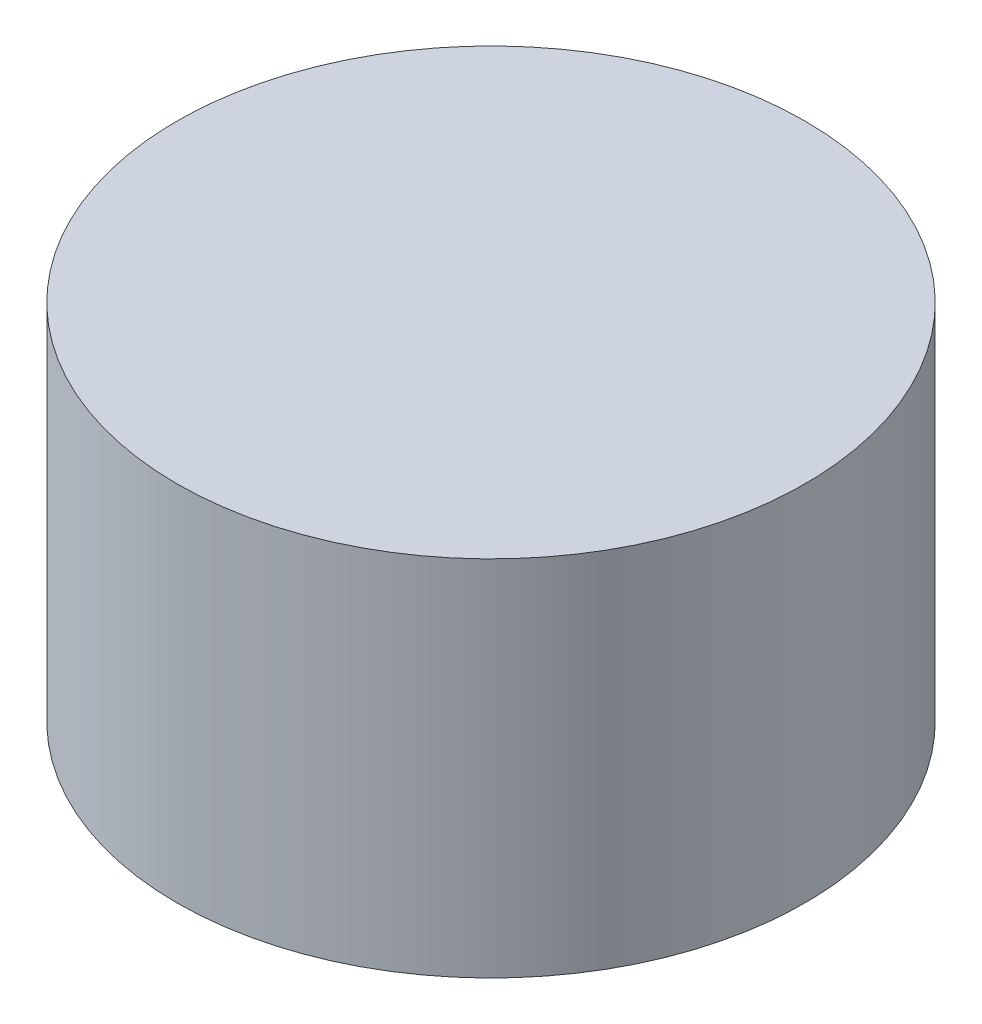
SolidWorks part; units mm, degrees
material "Бутил"
ref_plane "Спереди (XY)" through (0, 0, 0) normal (0, 0, 1) x (1, 0, 0)
ref_plane "Сверху (XZ)" through (0, 0, 0) normal (0, 1, 0) x (1, 0, 0)
ref_plane "Справа (ZY)" through (0, 0, 0) normal (1, 0, 0) x (0, 0, -1)
sketch "Эскиз1" plane through (0, 0, 0) normal (0, 1, 0) x (1, 0, 0)
  circle A0 centre (0, 0) radius 45
  dimension "D1" = 90
extrude "Бобышка-Вытянуть1" add sketch "Эскиз1" along normal blind 52
